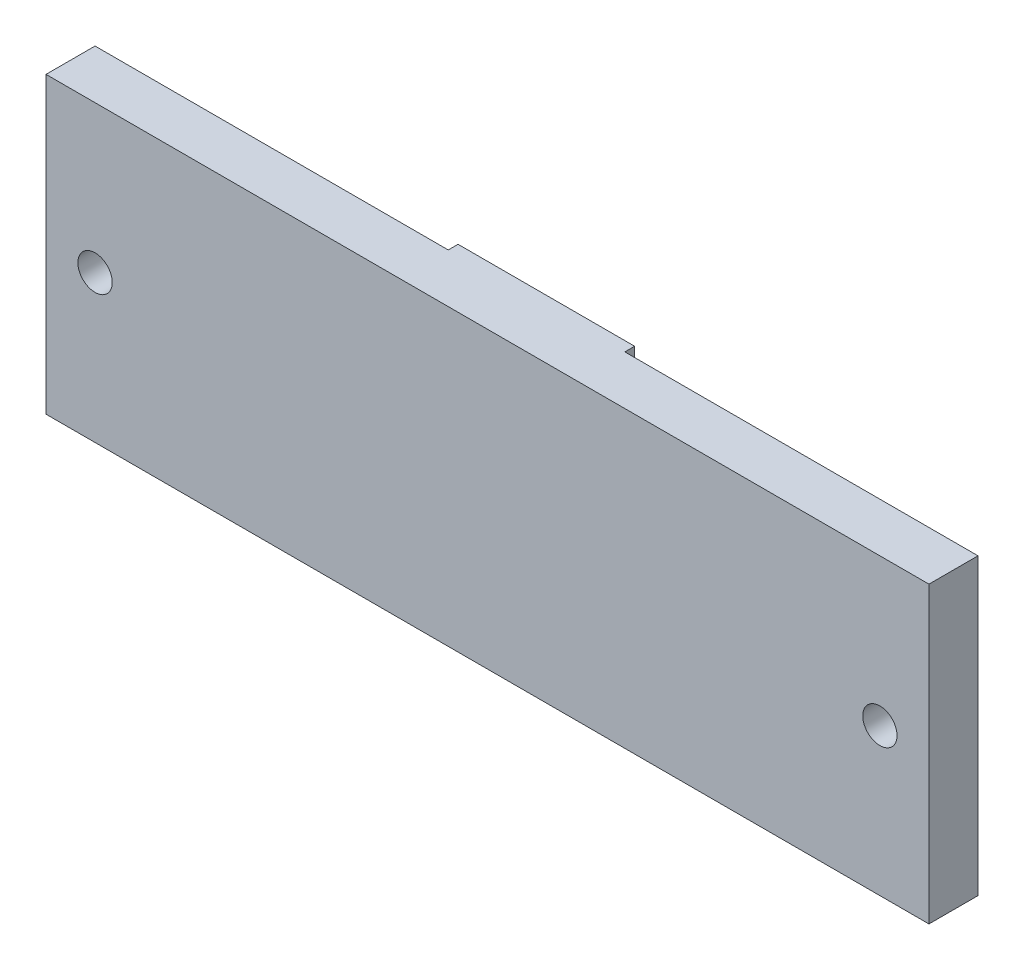
SolidWorks part; units mm, degrees
ref_plane "Front Plane" through (0, 0, 0) normal (0, 0, 1) x (1, 0, 0)
ref_plane "Top Plane" through (0, 0, 0) normal (0, 1, 0) x (1, 0, 0)
ref_plane "Right Plane" through (0, 0, 0) normal (1, 0, 0) x (0, 0, -1)
sketch "Sketch1" plane through (0, 0, 0) normal (0, 0, 1) x (1, 0, 0)
  line L1 (45, 0) -> (-45, 0)
  line L2 (45, 0) -> (45, -30)
  line L3 (45, -30) -> (-45, -30)
  line L4 (-45, 0) -> (-45, -30)
extrude "Boss-Extrude1" add sketch "Sketch1" along normal blind 5
sketch "Sketch2" plane through (0, 0, 5) normal (0, 0, 1) x (1, 0, 0)
  circle A0 centre (40, -15) radius 1.75
  circle A1 centre (-40, -15) radius 1.75
  dimension "D1" = 3.5
extrude "Cut-Extrude1" cut sketch "Sketch2" against normal through all
sketch "Sketch3" plane through (0, 0, 0) normal (0, 0, -1) x (-1, 0, 0)
  line L0 (-45, 0) -> (45, 0) construction
  line L1 (-9, 0) -> (9, 0)
  line L2 (-9, 0) -> (-9, -30)
  line L3 (-9, -30) -> (9, -30)
  line L4 (9, 0) -> (9, -30)
  line L5 (45, -30) -> (-45, -30) construction
  point P8 (0, 0)
  point P9 (0, 0)
  dimension "D1" = 18
extrude "Boss-Extrude2" add sketch "Sketch3" along normal blind 1
